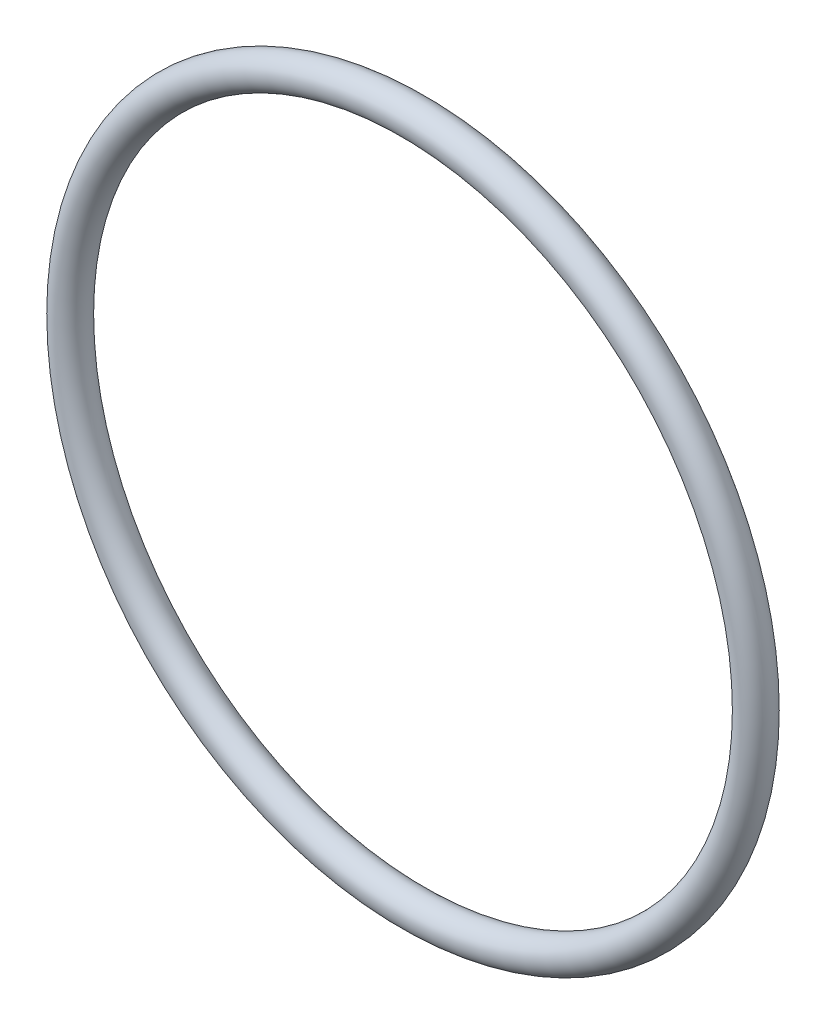
SolidWorks part; units mm, degrees
ref_plane "Front" through (0, 0, 0) normal (0, 0, 1) x (1, 0, 0)
ref_plane "Top" through (0, 0, 0) normal (0, 1, 0) x (1, 0, 0)
ref_plane "Right" through (0, 0, 0) normal (1, 0, 0) x (0, 0, -1)
sketch "Sketch1" plane through (0, 0, 0) normal (1, 0, 0) x (0, -1, 0)
  line L0 (0, -1.7653) -> (0, 1.7653) construction
  line L2 (-42.0776, 0) -> (42.0776, 0) construction
  line L3 (-34.7218, 0) -> (34.7218, 0) construction
  circle A0 centre (36.4871, 0) radius 1.7653
  point P9 (34.7218, 0)
  point P10 (38.2524, 0)
  point P13 (36.4871, 1.7653)
  point P14 (36.4871, -1.7653)
  dimension "Width" = 3.5306
  dimension "ID" = 69.4436
revolve "Revolve1" add sketch "Sketch1" angle 360 about L0
ref_plane "Plane1" through (0, 0, 1.7653) normal (0, 0, 1) x (1, 0, 0)
sketch "Sketch2" plane through (0, 0, 1.7653) normal (0, 0, 1) x (1, 0, 0)
  circle A0 centre (0, 0) radius 36.4871
